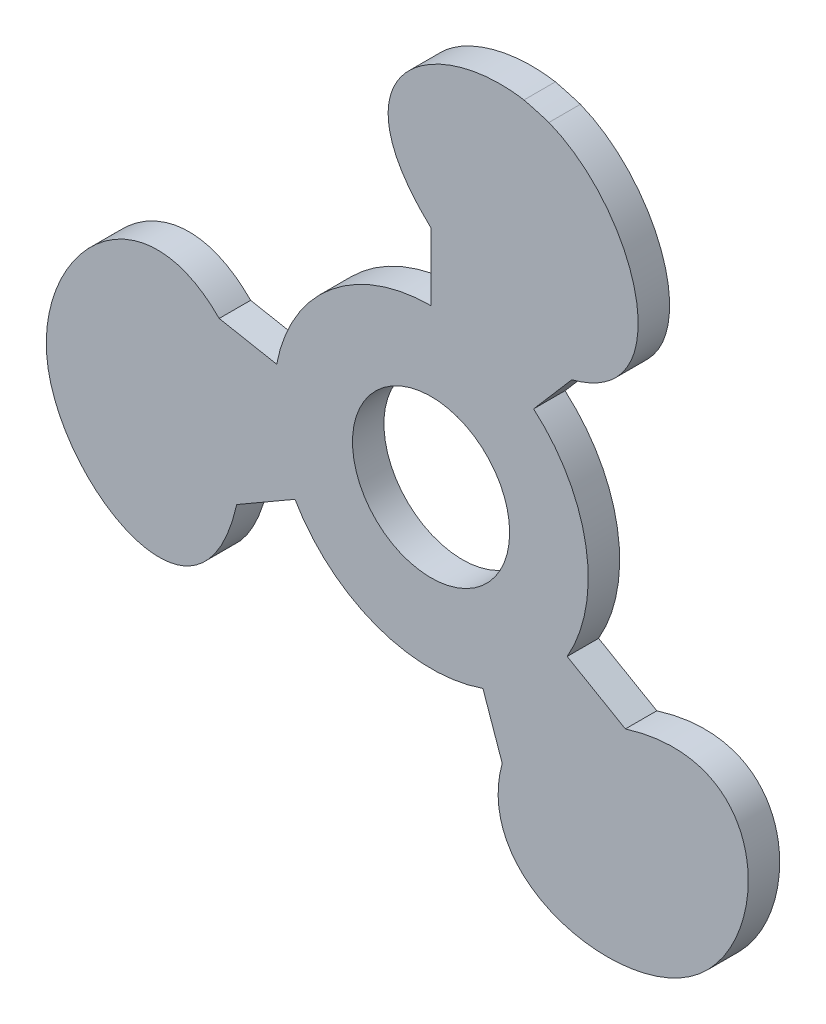
SolidWorks part; units mm, degrees
ref_plane "前视基准面" through (0, 0, 0) normal (0, 0, 1) x (1, 0, 0)
ref_plane "上视基准面" through (0, 0, 0) normal (0, 1, 0) x (1, 0, 0)
ref_plane "右视基准面" through (0, 0, 0) normal (1, 0, 0) x (0, 0, -1)
sketch "草图1" plane through (0, 0, 0) normal (0, 0, 1) x (1, 0, 0)
  line L0 (0, 5) -> (0, 14.2782)
  line L1 (8.955, 10.3977) -> (3.2629, 3.7886)
  line L2 (4.3301, -2.5) -> (12.3653, -7.1391)
  line L3 (4.5272, -12.9541) -> (1.6496, -4.7201)
  line L4 (-4.3301, -2.5) -> (-12.3653, -7.1391)
  line L5 (-13.4822, 2.5564) -> (-4.9125, 0.9315)
  arc A0 (7.4996, 23.8486) -> (5.9096, 24.2915) centre (0, 0) ccw
  arc A1 (0, 5) -> (-4.9125, 0.9315) centre (0, 0) ccw
  arc A2 (-4.3301, -2.5) -> (1.6496, -4.7201) centre (0, 0) ccw
  arc A3 (4.3301, -2.5) -> (3.2629, 3.7886) centre (0, 0) ccw
  spline S0 degree 3 poles (0, 14.2782) (-7.267, 21.0013) (10.208, 31.2065) (16.0984, 12.2695) (8.955, 10.3977) knots 0 0 0 0 0.508066 1 1 1 1
  spline S1 degree 3 poles (12.3653, -7.1391) (21.8211, -4.2072) (21.9216, -24.4436) (2.5765, -20.0764) (4.5272, -12.9541) knots 0 0 0 0 0.508066 1 1 1 1
  spline S2 degree 3 poles (-12.3653, -7.1391) (-14.5542, -16.794) (-32.1296, -6.7629) (-18.6749, 7.8069) (-13.4822, 2.5564) knots 0 0 0 0 0.508066 1 1 1 1
  point P28 (0, 0)
  dimension "D1" = 50
  dimension "D2" = 10
  dimension "D3" = 3
extrude "凸台-拉伸1" add sketch "草图1" along normal blind 2 contours S2 L4 A2 L3 S1 L2 A3 L1 S0 A0 L0 A1 L5
sketch "草图2" plane through (0, 0, 2) normal (0, 0, 1) x (1, 0, 0)
  circle A0 centre (0, 0) radius 10
  dimension "D1" = 20
extrude "凸台-拉伸2" add sketch "草图2" against normal blind 2
sketch "草图3" plane through (0, 0, 2) normal (0, 0, 1) x (1, 0, 0)
  circle A0 centre (0, 0) radius 5
  dimension "D1" = 10
extrude "切除-拉伸1" cut sketch "草图3" against normal blind 2
